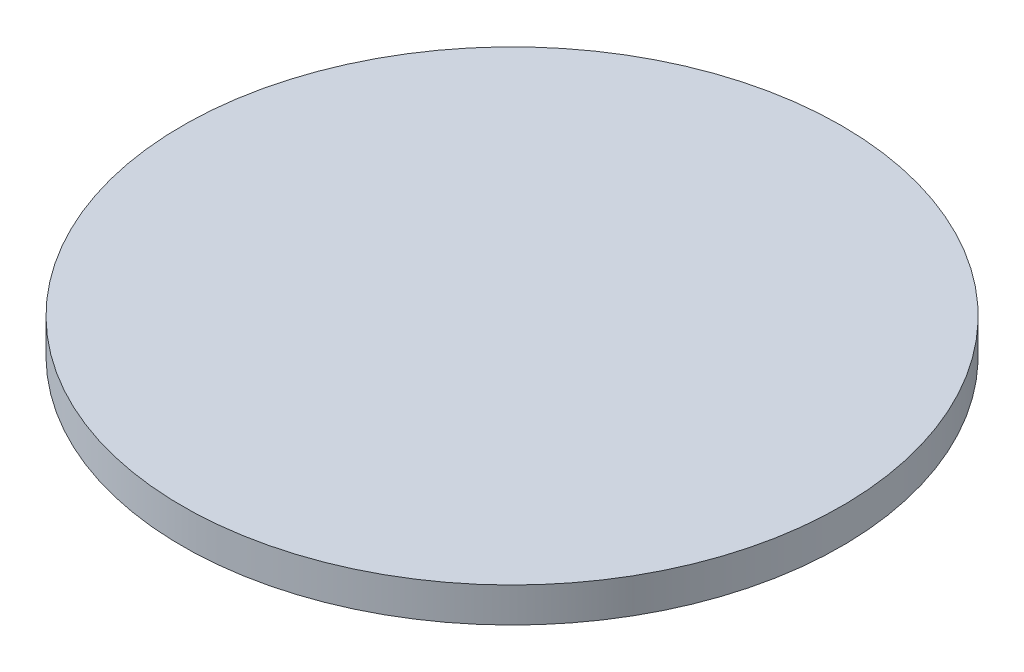
SolidWorks part; units mm, degrees
ref_plane "Front Plane" through (0, 0, 0) normal (0, 0, 1) x (1, 0, 0)
ref_plane "Top Plane" through (0, 0, 0) normal (0, 1, 0) x (1, 0, 0)
ref_plane "Right Plane" through (0, 0, 0) normal (1, 0, 0) x (0, 0, -1)
sketch "Sketch1" plane through (0, 0, 0) normal (0, 0, 1) x (1, 0, 0)
  line L1 (0, 0) -> (0, 6)
  line L2 (-3, 3) -> (-2.1, 3)
  line L3 (-2.1, 3) -> (-2.1, 5)
  line L4 (-2.1, 5) -> (-9.5, 5)
  line L7 (0, 6) -> (0, 0) construction
  line L8 (-3, 3) -> (-2.1, 0)
  line L9 (-2.1, 0) -> (0, 0)
  line L11 (0, 0) -> (0, 6) construction
  line L12 (-9.5, 5) -> (-9.5, 6)
  line L13 (-9.5, 6) -> (0, 6)
  dimension "D1" = 2
  dimension "D2" = 0
  dimension "D3" = 2.1
  dimension "D4" = 3
  dimension "D5" = 1
  dimension "D6" = 3
  dimension "D7" = 2.1
  dimension "D8" = 9.5
revolve "Revolve1" add sketch "Sketch1" angle 360 about L1
